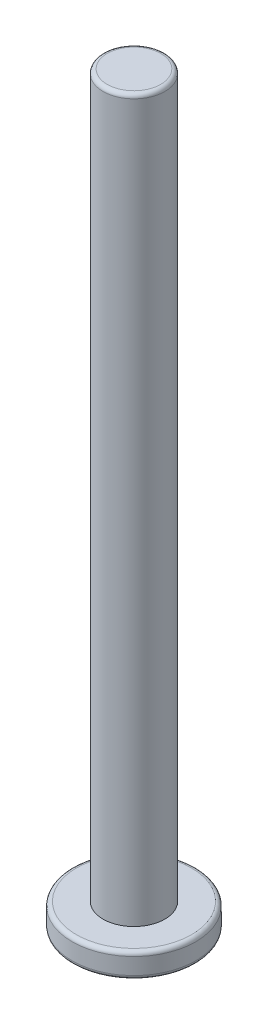
SolidWorks part; units mm, degrees
ref_plane "Front Plane" through (0, 0, 0) normal (0, 0, 1) x (1, 0, 0)
ref_plane "Top Plane" through (0, 0, 0) normal (0, 1, 0) x (1, 0, 0)
ref_plane "Right Plane" through (0, 0, 0) normal (1, 0, 0) x (0, 0, -1)
sketch "Sketch2" plane through (0, 0, 0) normal (0, 0, 1) x (1, 0, 0)
  line L0 (0, 0) -> (3, 0)
  line L1 (3, 0) -> (3, 1.2)
  line L2 (3, 1.2) -> (1.5, 1.2)
  line L3 (1.5, 1.2) -> (1.5, 36.2)
  line L4 (1.5, 36.2) -> (0, 36.2)
  line L5 (0, 36.2) -> (0, 0)
  line L6 (0, 73.1143) -> (0, -37.0787) construction
  dimension "D1" = 3
  dimension "D2" = 35
  dimension "D3" = 1.2
  dimension "D4" = 1.5
revolve "Revolve1" add sketch "Sketch2" angle 360 about L6
fillet "Fillet1" radius 0.2 3 edges at (0, 0, 3) (0, 1.2, 3) (0, 36.2, 1.5)
sketch "Sketch3" plane through (0, 0, 0) normal (0, -1, 0) x (1, 0, 0)
  line L1 (1.4434, 0) -> (0.7217, 1.25)
  line L2 (0.7217, 1.25) -> (-0.7217, 1.25)
  line L3 (-0.7217, 1.25) -> (-1.4434, 0)
  line L4 (-1.4434, 0) -> (-0.7217, -1.25)
  line L5 (-0.7217, -1.25) -> (0.7217, -1.25)
  line L6 (0.7217, -1.25) -> (1.4434, 0)
  circle A0 centre (0, 0) radius 1.25 construction
  dimension "D1" = 2.5
extrude "Cut-Extrude1" cut sketch "Sketch3" against normal blind 1
